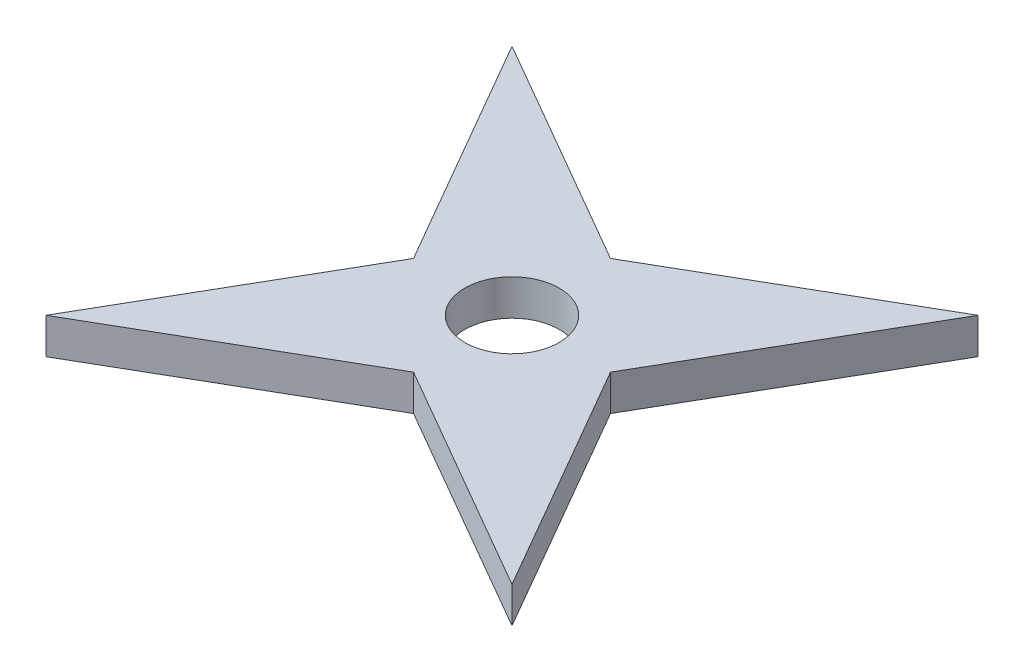
SolidWorks part; units mm, degrees
ref_plane "Front Plane" through (0, 0, 0) normal (0, 0, 1) x (1, 0, 0)
ref_plane "Top Plane" through (0, 0, 0) normal (0, 1, 0) x (1, 0, 0)
ref_plane "Right Plane" through (0, 0, 0) normal (1, 0, 0) x (0, 0, -1)
sketch "Sketch1" plane through (0, 0, 0) normal (0, 1, 0) x (1, 0, 0)
  line L0 (0, 0) -> (0, 234.4789) construction
  line L1 (0, 0) -> (250.2537, 0) construction
  line L2 (0, 0) -> (37.5, 64.9519)
  line L3 (0, 0) -> (64.9519, 37.5)
  line L5 (64.9519, 64.9519) -> (64.9519, 0) construction
  line L6 (129.9038, 0) -> (64.9519, 37.5)
  line L7 (129.9038, 0) -> (92.4038, 64.9519)
  line L8 (37.5, 64.9519) -> (92.4038, 64.9519) construction
  line L9 (129.9038, 129.9038) -> (92.4038, 64.9519)
  line L10 (129.9038, 129.9038) -> (64.9519, 92.4038)
  line L11 (0, 129.9038) -> (64.9519, 92.4038)
  line L12 (0, 129.9038) -> (37.5, 64.9519)
  circle A0 centre (64.9519, 64.9519) radius 13.155
  dimension "D5" = 26.31
  dimension "D1" = 75
  dimension "D2" = 30
  dimension "D3" = 30
  dimension "D4" = 75
extrude "Boss-Extrude1" add sketch "Sketch1" along normal blind 10
